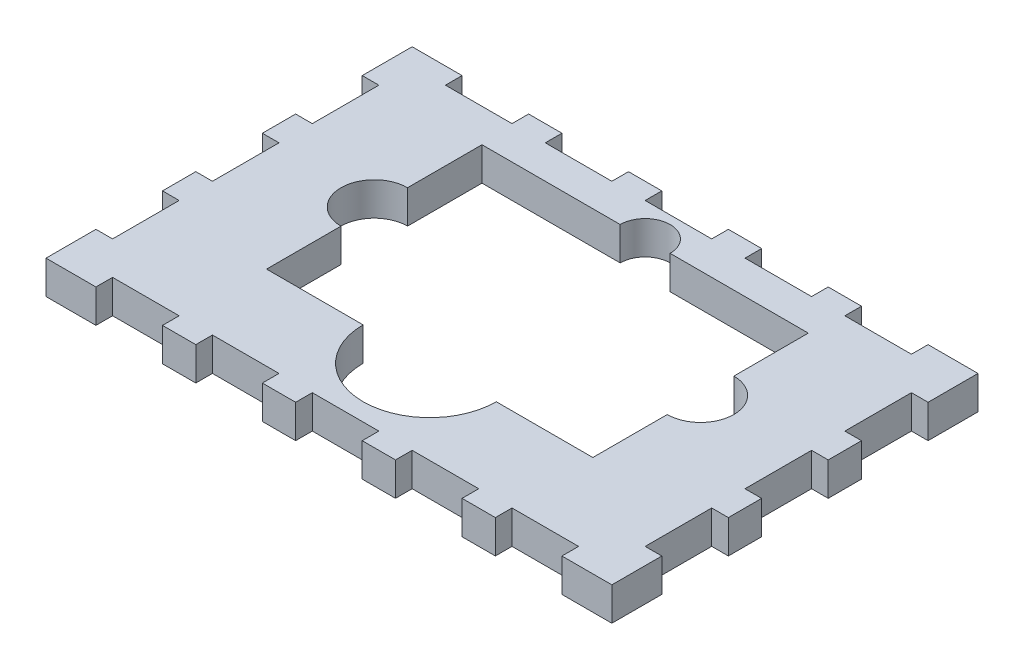
SolidWorks part; units mm, degrees
ref_plane "Front Plane" through (0, 0, 0) normal (0, 0, 1) x (1, 0, 0)
ref_plane "Top Plane" through (0, 0, 0) normal (0, 1, 0) x (1, 0, 0)
ref_plane "Right Plane" through (0, 0, 0) normal (1, 0, 0) x (0, 0, -1)
sketch "Sketch7" plane through (0, 0, 0) normal (0, 1, 0) x (1, 0, 0)
  line L1 (101.6, 63.5) -> (-101.6, 63.5)
  line L2 (101.6, 63.5) -> (101.6, -63.5)
  line L3 (101.6, -63.5) -> (-101.6, -63.5)
  line L4 (-101.6, 63.5) -> (-101.6, -63.5)
  line L5 (0, -63.5) -> (0, 63.5) construction
  line L6 (101.6, 0) -> (-101.6, 0) construction
  line L7 (-62.25, 50.8) -> (62.25, 50.8)
  line L8 (-62.25, 50.8) -> (-62.25, -31.4)
  line L9 (-62.25, -31.4) -> (62.25, -31.4)
  line L10 (62.25, 50.8) -> (62.25, -31.4)
  line L78 (-63.754, 177.8) -> (-101.6, 177.8) construction
  line L79 (63.754, 177.8) -> (101.6, 177.8) construction
  point P0 (0, 0)
  point P4 (0, 50.8)
  dimension "D1" = 124.5
  dimension "D2" = 82.2
  dimension "D3" = 127
  dimension "D9" = 203.2
  dimension "D4" = 12.7
extrude "Boss-Extrude4" add sketch "Sketch7" along normal blind 12.7
sketch "Sketch8" plane through (0, 0, 0) normal (0, 1, 0) x (1, 0, 0)
  line L1 (-101.6, 69.85) -> (-88.9, 69.85)
  line L2 (-88.9, 69.85) -> (-88.9, 63.5)
  line L3 (101.6, 63.5) -> (-101.6, 63.5) construction
  line L5 (-63.5, 63.5) -> (-63.5, 69.85)
  line L6 (-63.5, 69.85) -> (-50.8, 69.85)
  line L7 (-50.8, 69.85) -> (-50.8, 63.5)
  line L8 (-63.5, 63.5) -> (-50.8, 63.5)
  line L9 (-25.4, 63.5) -> (-25.4, 69.85)
  line L10 (-25.4, 69.85) -> (-12.7, 69.85)
  line L11 (-12.7, 69.85) -> (-12.7, 63.5)
  line L12 (-25.4, 63.5) -> (-12.7, 63.5)
  line L13 (12.7, 63.5) -> (12.7, 69.85)
  line L14 (12.7, 69.85) -> (25.4, 69.85)
  line L15 (25.4, 69.85) -> (25.4, 63.5)
  line L16 (12.7, 63.5) -> (25.4, 63.5)
  line L29 (50.8, 63.5) -> (50.8, 69.85)
  line L59 (-101.6, 63.5) -> (-101.6, -63.5) construction
  line L60 (-107.95, 63.5) -> (-107.95, 50.8)
  line L61 (-107.95, 50.8) -> (-101.6, 50.8)
  line L63 (-107.95, 12.7) -> (-101.6, 12.7)
  line L64 (-101.6, 25.4) -> (-101.6, 12.7)
  line L65 (-101.6, 25.4) -> (-107.95, 25.4)
  line L66 (-107.95, 25.4) -> (-107.95, 12.7)
  line L67 (-107.95, -25.4) -> (-101.6, -25.4)
  line L68 (-101.6, -12.7) -> (-101.6, -25.4)
  line L69 (-101.6, -12.7) -> (-107.95, -12.7)
  line L70 (-107.95, -12.7) -> (-107.95, -25.4)
  line L95 (50.8, 69.85) -> (63.5, 69.85)
  line L132 (-107.95, -177.8) -> (-101.6, -177.8) [skipped]
  line L133 (-101.6, -50.8) -> (-88.9, -63.5)
  line L134 (-107.95, -69.85) -> (-101.6, -69.85)
  line L135 (-107.95, -165.1) -> (-107.95, -177.8) [skipped]
  line L136 (-107.95, -215.9) -> (-101.6, -215.9) [skipped]
  line L137 (-107.95, -63.5) -> (-107.95, -69.85)
  line L138 (-107.95, -50.8) -> (-101.6, -50.8)
  line L139 (-107.95, -203.2) -> (-107.95, -215.9) [skipped]
  line L140 (-107.95, -63.5) -> (-107.95, -50.8)
  line L141 (-88.9, -69.85) -> (-88.9, -63.5)
  line L142 (-107.95, -241.3) -> (-107.95, -254) [skipped]
  line L143 (-107.95, -254) -> (-101.6, -254) [skipped]
  line L144 (63.5, 69.85) -> (63.5, 63.5) [skipped]
  line L145 (-101.6, -69.85) -> (-88.9, -69.85)
  line L146 (88.9, 69.85) -> (101.6, 69.85) [skipped]
  line L147 (101.6, 69.85) -> (101.6, 63.5) [skipped]
  line L148 (101.6, 50.8) -> (88.9, 63.5)
  line L149 (50.8, 69.85) -> (63.5, 69.85) [skipped]
  line L150 (107.95, 69.85) -> (101.6, 69.85)
  line L151 (107.95, 63.5) -> (107.95, 69.85)
  line L152 (107.95, 50.8) -> (101.6, 50.8)
  line L153 (127, 69.85) -> (139.7, 69.85) [skipped]
  line L154 (107.95, 63.5) -> (107.95, 50.8)
  line L155 (139.7, 69.85) -> (139.7, 63.5) [skipped]
  line L164 (-107.95, -101.6) -> (-101.6, -101.6) [skipped]
  line L165 (88.9, 69.85) -> (88.9, 63.5)
  line L166 (101.6, 69.85) -> (88.9, 69.85)
  line L167 (-107.95, -88.9) -> (-107.95, -101.6) [skipped]
  line L168 (-107.95, -139.7) -> (-101.6, -139.7) [skipped]
  line L169 (101.6, -69.85) -> (88.9, -69.85)
  line L170 (88.9, -69.85) -> (88.9, -63.5)
  line L171 (-107.95, -127) -> (-107.95, -139.7) [skipped]
  line L196 (63.5, 69.85) -> (63.5, 63.5)
  line L197 (50.8, 63.5) -> (63.5, 63.5)
  line L198 (0, 0) -> (0, -63.5) construction
  line L199 (-101.6, -63.5) -> (101.6, -63.5) construction
  line L200 (0, 0) -> (101.6, 0) construction
  line L201 (101.6, -63.5) -> (101.6, 63.5) construction
  line L206 (107.95, -12.7) -> (107.95, -25.4)
  line L207 (101.6, -12.7) -> (107.95, -12.7)
  line L208 (101.6, -12.7) -> (101.6, -25.4)
  line L209 (107.95, -25.4) -> (101.6, -25.4)
  line L210 (107.95, 25.4) -> (107.95, 12.7)
  line L211 (101.6, 25.4) -> (107.95, 25.4)
  line L212 (101.6, 25.4) -> (101.6, 12.7)
  line L213 (107.95, 12.7) -> (101.6, 12.7)
  line L218 (50.8, -63.5) -> (63.5, -63.5)
  line L219 (63.5, -69.85) -> (63.5, -63.5)
  line L220 (50.8, -69.85) -> (63.5, -69.85)
  line L221 (50.8, -63.5) -> (50.8, -69.85)
  line L222 (12.7, -63.5) -> (25.4, -63.5)
  line L223 (25.4, -69.85) -> (25.4, -63.5)
  line L224 (12.7, -69.85) -> (25.4, -69.85)
  line L225 (12.7, -63.5) -> (12.7, -69.85)
  line L226 (-25.4, -63.5) -> (-12.7, -63.5)
  line L227 (-12.7, -69.85) -> (-12.7, -63.5)
  line L228 (-25.4, -69.85) -> (-12.7, -69.85)
  line L229 (-25.4, -63.5) -> (-25.4, -69.85)
  line L230 (-63.5, -63.5) -> (-50.8, -63.5)
  line L231 (-50.8, -69.85) -> (-50.8, -63.5)
  line L232 (-63.5, -69.85) -> (-50.8, -69.85)
  line L233 (-63.5, -63.5) -> (-63.5, -69.85)
  line L246 (101.6, 69.85) -> (101.6, 63.5) [skipped]
  line L247 (-107.95, -63.5) -> (-101.6, -63.5) [skipped]
  line L250 (-107.95, 63.5) -> (-107.95, 69.85)
  line L251 (-107.95, 69.85) -> (-101.6, 69.85)
  line L254 (-101.6, 50.8) -> (-88.9, 63.5)
  line L255 (107.95, -63.5) -> (107.95, -50.8)
  line L256 (107.95, -50.8) -> (101.6, -50.8)
  line L257 (107.95, -63.5) -> (107.95, -69.85)
  line L258 (-107.95, -50.8) -> (-107.95, -63.5) [skipped]
  line L259 (88.9, 63.5) -> (88.9, 69.85) [skipped]
  line L260 (88.9, 69.85) -> (101.6, 69.85) [skipped]
  line L261 (88.9, 63.5) -> (101.6, 63.5) [skipped]
  line L262 (107.95, -69.85) -> (101.6, -69.85)
  line L263 (101.6, -50.8) -> (88.9, -63.5)
  dimension "D1" = 12.7
  dimension "D4" = 7
  dimension "D5" = 25.4
  dimension "D6" = 3
  dimension "D13" = 25.4
  dimension "D9" = 9
extrude "Boss-Extrude5" add sketch "Sketch8" along normal blind 12.7
sketch "Sketch10" plane through (0, 12.7, 0) normal (0, 1, 0) x (1, 0, 0)
  line L0 (62.25, 50.8) -> (-62.25, 50.8) construction
  line L1 (-62.25, 50.8) -> (-62.25, -31.4) construction
  line L2 (-62.25, -31.4) -> (62.25, -31.4) construction
  line L3 (62.25, -31.4) -> (62.25, 50.8) construction
  circle A0 centre (0, 50.8) radius 9.525
  circle A1 centre (-62.25, 9.7) radius 12.7
  circle A2 centre (0, -31.4) radius 25.4
  circle A3 centre (62.25, 9.7) radius 12.7
  dimension "D1" = 19.05
  dimension "D2" = 50.8
  dimension "D3" = 25.4
extrude "Cut-Extrude1" cut sketch "Sketch10" against normal through all
